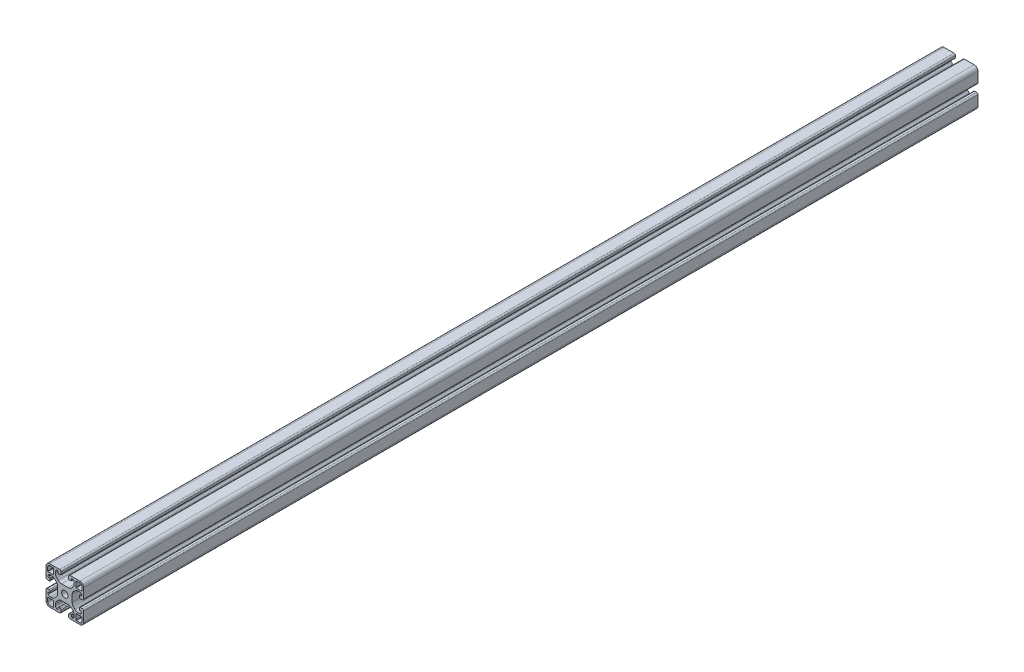
SolidWorks part; units mm, degrees
ref_plane "Plan de face" through (0, 0, 0) normal (0, 0, 1) x (1, 0, 0)
ref_plane "Plan de dessus" through (0, 0, 0) normal (0, 1, 0) x (1, 0, 0)
ref_plane "Plan de droite" through (0, 0, 0) normal (1, 0, 0) x (0, 0, -1)
ref_plane "Plan1" through (0, 0, -30) normal (0, 0, -1) x (-1, 0, 0)
sketch "Esquisse1" plane through (0, 0, -30) normal (0, 0, -1) x (-1, 0, 0)
  line L0 (-4.5, 15) -> (-4.5, 13.5)
  line L1 (-4, 13) -> (-2.5, 13)
  line L2 (-4.5, 10) -> (-5.8076, 10)
  line L3 (-9.3431, 11.4645) -> (-10.7855, 12.9069)
  line L4 (-12.25, 16.4424) -> (-12.25, 23.5576)
  line L5 (-10.7855, 27.0931) -> (-9.3431, 28.5355)
  line L6 (-5.8076, 30) -> (-4.5, 30)
  line L7 (-2.5, 27) -> (-4, 27)
  line L8 (-4.5, 26.5) -> (-4.5, 25)
  line L9 (-3.5, 24) -> (-1.5, 24)
  line L10 (0, 25.5) -> (0, 36)
  line L11 (-4, 40) -> (-14.5, 40)
  line L12 (-16, 38.5) -> (-16, 36.5)
  line L13 (-15, 35.5) -> (-13.5, 35.5)
  line L14 (-13, 36) -> (-13, 37.5)
  line L15 (-10, 35.5) -> (-10, 34.1924)
  line L16 (-11.4645, 30.6569) -> (-12.9069, 29.2145)
  line L17 (-16.4424, 27.75) -> (-23.5576, 27.75)
  line L18 (-27.0931, 29.2145) -> (-28.5355, 30.6569)
  line L19 (-30, 34.1924) -> (-30, 35.5)
  line L20 (-27, 37.5) -> (-27, 36)
  line L21 (-26.5, 35.5) -> (-25, 35.5)
  line L22 (-24, 36.5) -> (-24, 38.5)
  line L23 (-25.5, 40) -> (-36, 40)
  line L24 (-40, 36) -> (-40, 25.5)
  line L25 (-38.5, 24) -> (-36.5, 24)
  line L26 (-35.5, 25) -> (-35.5, 26.5)
  line L27 (-36, 27) -> (-37.5, 27)
  line L28 (-35.5, 30) -> (-34.1924, 30)
  line L29 (-30.6569, 28.5355) -> (-29.2145, 27.0931)
  line L30 (-27.75, 23.5576) -> (-27.75, 16.4424)
  line L31 (-29.2145, 12.9069) -> (-30.6569, 11.4645)
  line L32 (-34.1924, 10) -> (-35.5, 10)
  line L33 (-37.5, 13) -> (-36, 13)
  line L34 (-35.5, 13.5) -> (-35.5, 15)
  line L35 (-36.5, 16) -> (-38.5, 16)
  line L36 (-40, 14.5) -> (-40, 4)
  line L37 (-36, 0) -> (-25.5, 0)
  line L38 (-24, 1.5) -> (-24, 3.5)
  line L39 (-25, 4.5) -> (-26.5, 4.5)
  line L40 (-27, 4) -> (-27, 2.5)
  line L41 (-30, 4.5) -> (-30, 5.8076)
  line L42 (-28.5355, 9.3431) -> (-27.0931, 10.7855)
  line L43 (-23.5576, 12.25) -> (-16.4424, 12.25)
  line L44 (-12.9069, 10.7855) -> (-11.4645, 9.3431)
  line L45 (-10, 5.8076) -> (-10, 4.5)
  line L46 (-13, 2.5) -> (-13, 4)
  line L47 (-13.5, 4.5) -> (-15, 4.5)
  line L48 (-16, 3.5) -> (-16, 1.5)
  line L49 (-14.5, 0) -> (-4, 0)
  line L50 (0, 4) -> (0, 14.5)
  line L51 (-1.5, 16) -> (-3.5, 16)
  line L52 (-4, 1.8) -> (-7.7, 1.8)
  line L53 (-8.2, 2.3) -> (-8.2, 7.7)
  line L54 (-7.7, 8.2) -> (-2.3, 8.2)
  line L55 (-1.8, 7.7) -> (-1.8, 4)
  line L56 (-38.2, 4) -> (-38.2, 7.7)
  line L57 (-37.7, 8.2) -> (-32.3, 8.2)
  line L58 (-31.8, 7.7) -> (-31.8, 2.3)
  line L59 (-32.3, 1.8) -> (-36, 1.8)
  line L60 (-36, 38.2) -> (-32.3, 38.2)
  line L61 (-31.8, 37.7) -> (-31.8, 32.3)
  line L62 (-32.3, 31.8) -> (-37.7, 31.8)
  line L63 (-38.2, 32.3) -> (-38.2, 36)
  line L64 (-1.8, 36) -> (-1.8, 32.3)
  line L65 (-2.3, 31.8) -> (-7.7, 31.8)
  line L66 (-8.2, 32.3) -> (-8.2, 37.7)
  line L67 (-7.7, 38.2) -> (-4, 38.2)
  arc A0 (-4.5, 13.5) -> (-4, 13) centre (-4, 13.5) ccw
  arc A1 (-2.5, 13) -> (-2, 12.5) centre (-2.5, 12.5) cw
  arc A2 (-2, 12.5) -> (-4.5, 10) centre (-4.5, 12.5) cw
  arc A3 (-5.8076, 10) -> (-9.3431, 11.4645) centre (-5.8076, 15) cw
  arc A4 (-10.7855, 12.9069) -> (-12.25, 16.4424) centre (-7.25, 16.4424) cw
  arc A5 (-12.25, 23.5576) -> (-10.7855, 27.0931) centre (-7.25, 23.5576) cw
  arc A6 (-9.3431, 28.5355) -> (-5.8076, 30) centre (-5.8076, 25) cw
  arc A7 (-4.5, 30) -> (-2, 27.5) centre (-4.5, 27.5) cw
  arc A8 (-2, 27.5) -> (-2.5, 27) centre (-2.5, 27.5) cw
  arc A9 (-4, 27) -> (-4.5, 26.5) centre (-4, 26.5) ccw
  arc A10 (-4.5, 25) -> (-3.5, 24) centre (-3.5, 25) ccw
  arc A11 (-1.5, 24) -> (0, 25.5) centre (-1.5, 25.5) ccw
  arc A12 (0, 36) -> (-4, 40) centre (-4, 36) ccw
  arc A13 (-14.5, 40) -> (-16, 38.5) centre (-14.5, 38.5) ccw
  arc A14 (-16, 36.5) -> (-15, 35.5) centre (-15, 36.5) ccw
  arc A15 (-13.5, 35.5) -> (-13, 36) centre (-13.5, 36) ccw
  arc A16 (-13, 37.5) -> (-12.5, 38) centre (-12.5, 37.5) cw
  arc A17 (-12.5, 38) -> (-10, 35.5) centre (-12.5, 35.5) cw
  arc A18 (-10, 34.1924) -> (-11.4645, 30.6569) centre (-15, 34.1924) cw
  arc A19 (-12.9069, 29.2145) -> (-16.4424, 27.75) centre (-16.4424, 32.75) cw
  arc A20 (-23.5576, 27.75) -> (-27.0931, 29.2145) centre (-23.5576, 32.75) cw
  arc A21 (-28.5355, 30.6569) -> (-30, 34.1924) centre (-25, 34.1924) cw
  arc A22 (-30, 35.5) -> (-27.5, 38) centre (-27.5, 35.5) cw
  arc A23 (-27.5, 38) -> (-27, 37.5) centre (-27.5, 37.5) cw
  arc A24 (-27, 36) -> (-26.5, 35.5) centre (-26.5, 36) ccw
  arc A25 (-25, 35.5) -> (-24, 36.5) centre (-25, 36.5) ccw
  arc A26 (-24, 38.5) -> (-25.5, 40) centre (-25.5, 38.5) ccw
  arc A27 (-36, 40) -> (-40, 36) centre (-36, 36) ccw
  arc A28 (-40, 25.5) -> (-38.5, 24) centre (-38.5, 25.5) ccw
  arc A29 (-36.5, 24) -> (-35.5, 25) centre (-36.5, 25) ccw
  arc A30 (-35.5, 26.5) -> (-36, 27) centre (-36, 26.5) ccw
  arc A31 (-37.5, 27) -> (-38, 27.5) centre (-37.5, 27.5) cw
  arc A32 (-38, 27.5) -> (-35.5, 30) centre (-35.5, 27.5) cw
  arc A33 (-34.1924, 30) -> (-30.6569, 28.5355) centre (-34.1924, 25) cw
  arc A34 (-29.2145, 27.0931) -> (-27.75, 23.5576) centre (-32.75, 23.5576) cw
  arc A35 (-27.75, 16.4424) -> (-29.2145, 12.9069) centre (-32.75, 16.4424) cw
  arc A36 (-30.6569, 11.4645) -> (-34.1924, 10) centre (-34.1924, 15) cw
  arc A37 (-35.5, 10) -> (-38, 12.5) centre (-35.5, 12.5) cw
  arc A38 (-38, 12.5) -> (-37.5, 13) centre (-37.5, 12.5) cw
  arc A39 (-36, 13) -> (-35.5, 13.5) centre (-36, 13.5) ccw
  arc A40 (-35.5, 15) -> (-36.5, 16) centre (-36.5, 15) ccw
  arc A41 (-38.5, 16) -> (-40, 14.5) centre (-38.5, 14.5) ccw
  arc A42 (-40, 4) -> (-36, 0) centre (-36, 4) ccw
  arc A43 (-25.5, 0) -> (-24, 1.5) centre (-25.5, 1.5) ccw
  arc A44 (-24, 3.5) -> (-25, 4.5) centre (-25, 3.5) ccw
  arc A45 (-26.5, 4.5) -> (-27, 4) centre (-26.5, 4) ccw
  arc A46 (-27, 2.5) -> (-27.5, 2) centre (-27.5, 2.5) cw
  arc A47 (-27.5, 2) -> (-30, 4.5) centre (-27.5, 4.5) cw
  arc A48 (-30, 5.8076) -> (-28.5355, 9.3431) centre (-25, 5.8076) cw
  arc A49 (-27.0931, 10.7855) -> (-23.5576, 12.25) centre (-23.5576, 7.25) cw
  arc A50 (-16.4424, 12.25) -> (-12.9069, 10.7855) centre (-16.4424, 7.25) cw
  arc A51 (-11.4645, 9.3431) -> (-10, 5.8076) centre (-15, 5.8076) cw
  arc A52 (-10, 4.5) -> (-12.5, 2) centre (-12.5, 4.5) cw
  arc A53 (-12.5, 2) -> (-13, 2.5) centre (-12.5, 2.5) cw
  arc A54 (-13, 4) -> (-13.5, 4.5) centre (-13.5, 4) ccw
  arc A55 (-15, 4.5) -> (-16, 3.5) centre (-15, 3.5) ccw
  arc A56 (-16, 1.5) -> (-14.5, 0) centre (-14.5, 1.5) ccw
  arc A57 (-4, 0) -> (0, 4) centre (-4, 4) ccw
  arc A58 (0, 14.5) -> (-1.5, 16) centre (-1.5, 14.5) ccw
  arc A59 (-3.5, 16) -> (-4.5, 15) centre (-3.5, 15) ccw
  circle A60 centre (-20, 20) radius 3.4
  arc A61 (-1.8, 4) -> (-4, 1.8) centre (-4, 4) cw
  arc A62 (-7.7, 1.8) -> (-8.2, 2.3) centre (-7.7, 2.3) cw
  arc A63 (-8.2, 7.7) -> (-7.7, 8.2) centre (-7.7, 7.7) cw
  arc A64 (-2.3, 8.2) -> (-1.8, 7.7) centre (-2.3, 7.7) cw
  arc A65 (-36, 1.8) -> (-38.2, 4) centre (-36, 4) cw
  arc A66 (-38.2, 7.7) -> (-37.7, 8.2) centre (-37.7, 7.7) cw
  arc A67 (-32.3, 8.2) -> (-31.8, 7.7) centre (-32.3, 7.7) cw
  arc A68 (-31.8, 2.3) -> (-32.3, 1.8) centre (-32.3, 2.3) cw
  arc A69 (-38.2, 36) -> (-36, 38.2) centre (-36, 36) cw
  arc A70 (-32.3, 38.2) -> (-31.8, 37.7) centre (-32.3, 37.7) cw
  arc A71 (-31.8, 32.3) -> (-32.3, 31.8) centre (-32.3, 32.3) cw
  arc A72 (-37.7, 31.8) -> (-38.2, 32.3) centre (-37.7, 32.3) cw
  arc A73 (-4, 38.2) -> (-1.8, 36) centre (-4, 36) cw
  arc A74 (-1.8, 32.3) -> (-2.3, 31.8) centre (-2.3, 32.3) cw
  arc A75 (-7.7, 31.8) -> (-8.2, 32.3) centre (-7.7, 32.3) cw
  arc A76 (-8.2, 37.7) -> (-7.7, 38.2) centre (-7.7, 37.7) cw
extrude "Boss.-Extru.1" add sketch "Esquisse1" against normal blind 950
